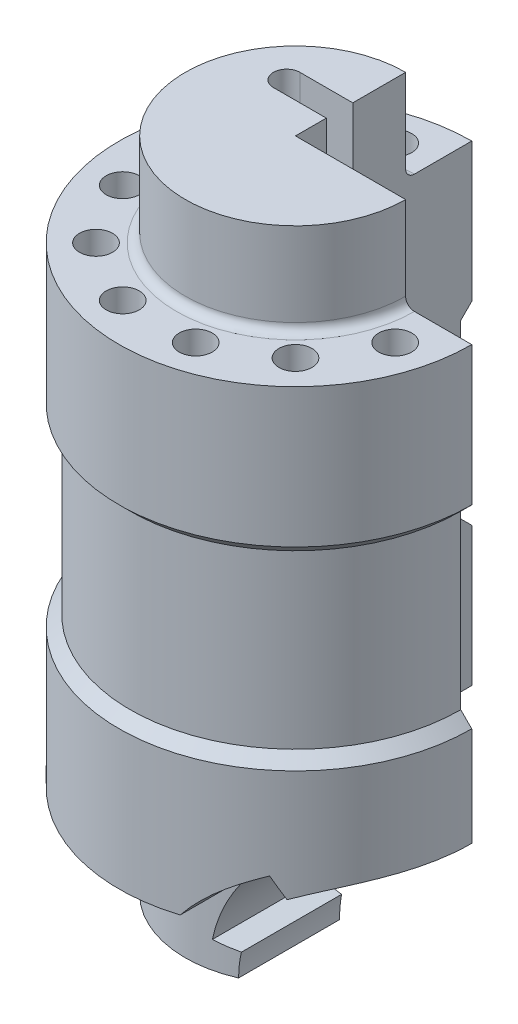
SolidWorks part; units mm, degrees
material "AISI 1020"
ref_plane "Front Plane" through (0, 0, 0) normal (0, 0, 1) x (1, 0, 0)
ref_plane "Top Plane" through (0, 0, 0) normal (0, 1, 0) x (1, 0, 0)
ref_plane "Right Plane" through (0, 0, 0) normal (1, 0, 0) x (0, 0, -1)
sketch "Sketch1" plane through (0, 0, 0) normal (0, 1, 0) x (1, 0, 0)
  circle A0 centre (0, 0) radius 40
  dimension "D1" = 80
extrude "Boss-Extrude1" add sketch "Sketch1" along normal mid plane 149
sketch "Sketch3" plane through (0, 74.5, 0) normal (0, 1, 0) x (1, 0, 0)
  circle A0 centre (0, 0) radius 25
  circle A1 centre (0, 0) radius 40 construction
  circle A2 centre (0, 0) radius 40
  dimension "D1" = 50
extrude "Cut-Extrude1" cut sketch "Sketch3" against normal blind 21 contours A2 | A0
mirror "Mirror1" about plane through (0, 0, 0) normal (0, 1, 0) of "Cut-Extrude1"
sketch "Sketch2" plane through (0, 0, 0) normal (0, 1, 0) x (1, 0, 0)
  circle A0 centre (0, 0) radius 37.5
  circle A1 centre (0, 0) radius 40 construction
  circle A2 centre (0, 0) radius 40
  dimension "D1" = 75
extrude "Cut-Extrude2" cut sketch "Sketch2" along normal offset from surface 31.5 and the other way offset from surface (22 mm away) 31.5 up to face at (0, 53.5, 25) other way up to face at (0, -53.5, 40)
sketch "Sketch5" plane through (0, 74.5, 0) normal (0, 1, 0) x (1, 0, 0)
  line L0 (0, -53.6027) -> (0, 7) construction
  line L1 (-43.3294, 0) -> (45.1465, 0) construction
  line L2 (-12, 10) -> (12, 10) construction
  line L3 (-12, 13) -> (12, 13)
  line L4 (-12, 7) -> (12, 7)
  line L6 (0, 13) -> (0, 49.2698) construction
  arc A0 (-12, 13) -> (-12, 7) centre (-12, 10) ccw
  arc A1 (12, 7) -> (12, 13) centre (12, 10) ccw
  point P7 (0, 10)
  dimension "D1" = 3
  dimension "D2" = 12
  dimension "D3" = 7
extrude "Cut-Extrude4" cut sketch "Sketch5" against normal through all
fillet "Fillet1" radius 2 2 edges at (0, -53.5, 25) (0, 53.5, 25)
chamfer "Chamfer1" [suppressed] distance 2.5 angle 45
sketch "Sketch7" plane through (0, 0, 0) normal (1, 0, 0) x (0, 0, -1)
  line L0 (40, 22) -> (37.5, 19.5)
  line L1 (37.5, -22) -> (37.5, 22) construction
  line L2 (40, 22) -> (40, 53.5) construction
  line L3 (40, 22) -> (37.5, 22)
  line L4 (37.5, 22) -> (37.5, 19.5)
  line L5 (0, 103.8814) -> (0, -88.9255) construction
  dimension "D1" = 45
  dimension "D2" = 2.5
revolve "Revolve2" add sketch "Sketch7" angle 360 about L5
mirror "Mirror2" about plane through (0, 0, 0) normal (0, 1, 0) of "Revolve2"
sketch "Sketch4" plane through (0, 74.5, 0) normal (0, 1, 0) x (1, 0, 0)
  line L0 (0, 0) -> (0, 40)
  line L1 (0, 0) -> (40, 0)
  circle A0 centre (0, 0) radius 40 construction
  arc A1 (40, 0) -> (0, 40) centre (0, 0) ccw
extrude "Cut-Extrude5" cut sketch "Sketch4" against normal through all
sketch "Sketch8" plane through (0, 53.5, 0) normal (0, 1, 0) x (1, 0, 0)
  line L0 (0, -45.9152) -> (0, 46.8029) construction
  line L1 (-43.3294, 0) -> (43.4692, 0) construction
  line L2 (0, 0) -> (-12.5822, 46.9576) construction
  line L3 (0, 0) -> (43.6258, -11.6895) construction
  line L4 (0, 0) -> (22.6274, -22.6274) construction
  line L5 (0, 0) -> (10.3528, -38.637) construction
  line L6 (0, 0) -> (-8.2822, -30.9096) construction
  line L7 (0, 0) -> (-22.6274, -22.6274) construction
  line L8 (0, 0) -> (-30.9096, -8.2822) construction
  line L9 (0, 0) -> (-30.9096, 8.2822) construction
  line L10 (0, 0) -> (-22.6274, 22.6274) construction
  circle A1 centre (0, 0) radius 32 construction
  circle A3 centre (-8.2822, 30.9096) radius 3.75
  circle A4 centre (30.9096, -8.2822) radius 3.75
  circle A5 centre (22.6274, -22.6274) radius 3.75
  circle A12 centre (16.353, 18.0359) radius 3.75 [skipped]
  circle A13 centre (-0.2003, 18.6445) radius 3.75 [skipped]
  circle A14 centre (-13.2094, 8.3907) radius 3.75 [skipped]
  circle A15 centre (-16.4846, -7.8468) radius 3.75 [skipped]
  circle A16 centre (-8.4673, -22.3417) radius 3.75 [skipped]
  circle A17 centre (7.0275, -28.1973) radius 3.75 [skipped]
  arc A18 (0, 40) -> (40, 0) centre (0, 0) ccw construction
  circle A19 centre (8.2822, -30.9096) radius 3.75
  circle A20 centre (-8.2822, -30.9096) radius 3.75
  circle A22 centre (-22.6274, -22.6274) radius 3.75
  circle A23 centre (-30.9096, -8.2822) radius 3.75
  circle A24 centre (-30.9096, 8.2822) radius 3.75
  circle A25 centre (-22.6274, 22.6274) radius 3.75
  point P28 (-11.024, -34.0902)
  point P29 (0, 0)
  point P30 (0, 0)
  point P51 (0, 0)
  point P52 (0, 0)
  point P53 (-9.128, -25.4102)
  point P54 (-8.2822, -25.6824)
  point P55 (0, 0)
  dimension "D2" = 64
  dimension "D3" = 7.5
  dimension "D1" = 15
  dimension "D4" = 15
  dimension "D6" = 30
  dimension "D7" = 30
  dimension "D8" = 15
  dimension "D9" = 30
  dimension "D10" = 30
  dimension "D11" = 30
  dimension "D12" = 30
  dimension "D5" = 8
extrude "Cut-Extrude6" cut sketch "Sketch8" against normal through all
sketch "Sketch10" plane through (0, 0, 0) normal (0, 0, -1) x (-1, 0, 0)
  line L0 (-10, -74.5) -> (-64.1408, -74.5) construction
  line L1 (-40, -44.5) -> (-40, -97.186) construction
  line L2 (-40, -53.5) -> (-40, -22) construction
  line L3 (-27.3215, -47.3108) -> (-25.2084, -42.7792)
  line L4 (-10.4558, -69.2906) -> (-5.5317, -68.4223)
  line L5 (-40, -53.5) -> (-40, -44.5)
  line L6 (-40, -53.5) -> (-27, -53.5) construction
  line L7 (-40, -53.5) -> (-27, -53.5)
  line L8 (-25, -74.5) -> (-25, -55.5) construction
  line L9 (-25, -74.5) -> (-25, -55.5)
  line L10 (-27.3215, -47.3108) -> (-40, -74.5) construction
  line L11 (-10.4558, -69.2906) -> (-40, -74.5) construction
  line L22 (-25, -74.5) -> (0, -74.5)
  line L23 (0, -74.5) -> (0, 74.5)
  line L24 (0, 74.5) -> (-25, 74.5)
  line L25 (-25, 74.5) -> (-25, 55.5)
  line L26 (-27, 53.5) -> (-40, 53.5)
  line L27 (-40, 53.5) -> (-40, 22)
  line L28 (-40, 22) -> (-37.5, 19.5)
  line L29 (-37.5, 19.5) -> (-37.5, -19.5)
  line L30 (-37.5, -19.5) -> (-40, -22)
  line L31 (-40, -22) -> (-40, -53.5)
  line L32 (-40, -53.5) -> (-27, -53.5)
  line L33 (-25, -55.5) -> (-25, -74.5)
  line L34 (-25, -74.5) -> (-10, -74.5)
  line L43 (-40, -44.5) -> (-40, -53.5)
  line L44 (-40, -53.5) -> (-27, -53.5)
  line L45 (-25, -55.5) -> (-25, -74.5)
  arc A2 (-5.5317, -68.4223) -> (-25.2084, -42.7792) centre (-40, -74.5) ccw
  arc A3 (-10, -74.5) -> (-10.4558, -69.2906) centre (-40, -74.5) ccw
  arc A4 (-25, -55.5) -> (-27, -53.5) centre (-27, -55.5) ccw construction
  arc A5 (-25, -55.5) -> (-27, -53.5) centre (-27, -55.5) ccw
  arc A6 (-27.3215, -47.3108) -> (-40, -44.5) centre (-40, -74.5) ccw
  arc A8 (-27, 53.5) -> (-25, 55.5) centre (-27, 55.5) ccw
  arc A9 (-25, -55.5) -> (-27, -53.5) centre (-27, -55.5) ccw
  arc A11 (-25, -55.5) -> (-27, -53.5) centre (-27, -55.5) ccw
  point P17 (0, 0)
  line M23 (-25, -74.5) -> (0, -74.5)
  line M33 (-40, -22) -> (-40, -53.5)
  line M34 (-40, -53.5) -> (-27, -53.5)
  arc M35 (-27, -53.5) -> (-25, -55.5) centre (-27, -55.5) cw
  line M36 (-25, -55.5) -> (-25, -74.5)
  dimension "D1" = 70
  dimension "D2" = 60
  dimension "D6" = 5
  dimension "D3" = 25
  dimension "D4" = 10
  dimension "D5" = 0
extrude "Cut-Extrude7" cut sketch "Sketch10" against normal through all contours L3 A6 A3 L4 A2 M33 M34 M35 M36 M23
equation "\"A\"= 149"
equation "\"B\"= 21"
equation "\"C\" = 31.5"
equation "\"D1@Boss-Extrude1\"=\"A\""
equation "\"D1@Cut-Extrude1\"=\"B\""
equation "\"D1@Cut-Extrude2\"=\"C\""
equation "\"D2@Cut-Extrude2\"=\"C\""
equation "\"D7@Sketch8\"=\"D6@Sketch8\""
equation "\"D8@Sketch8\"=\"D1@Sketch8\""
equation "\"D9@Sketch8\"=\"D6@Sketch8\""
equation "\"D10@Sketch8\"=\"D6@Sketch8\""
equation "\"D11@Sketch8\"=\"D6@Sketch8\""
equation "\"D12@Sketch8\"=\"D6@Sketch8\""
equation "\"D4@Sketch8\"=\"D1@Sketch8\""
